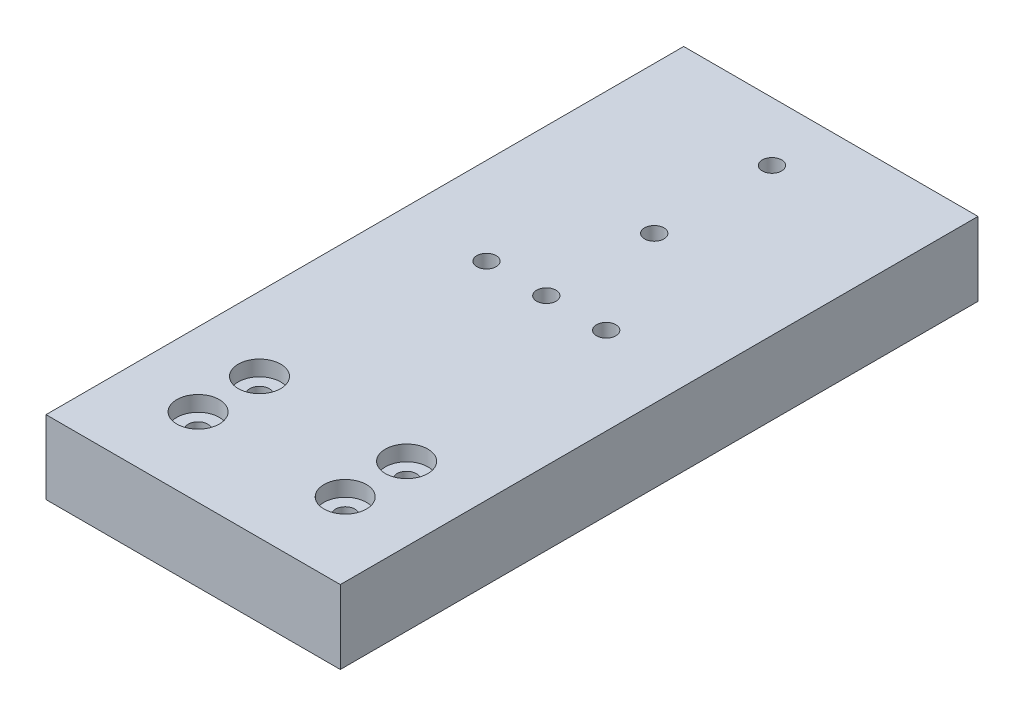
SolidWorks part; units mm, degrees
ref_plane "Front Plane" through (0, 0, 0) normal (0, 0, 1) x (1, 0, 0)
ref_plane "Top Plane" through (0, 0, 0) normal (0, 1, 0) x (1, 0, 0)
ref_plane "Right Plane" through (0, 0, 0) normal (1, 0, 0) x (0, 0, -1)
sketch "Sketch1" plane through (0, 0, 0) normal (0, 1, 0) x (1, 0, 0)
  line L1 (0, 0) -> (38.1, 0)
  line L2 (0, 0) -> (0, 82.55)
  line L3 (0, 82.55) -> (38.1, 82.55)
  line L4 (38.1, 0) -> (38.1, 82.55)
  line L5 (0, 0) -> (38.1, 82.55) construction
  line L6 (0, 82.55) -> (38.1, 0) construction
  point P4 (19.05, 41.275)
  dimension "D1" = 82.55
  dimension "D2" = 38.1
extrude "Boss-Extrude1" add sketch "Sketch1" along normal blind 9.525
sketch "Sketch2" plane through (0, 0, 0) normal (0, -1, 0) x (1, 0, 0)
  line L0 (0, -82.55) -> (0, 0) construction
  line L1 (38.1, -82.55) -> (0, -82.55) construction
  line L2 (38.1, -82.55) -> (38.1, -52.07) construction
  line L3 (38.1, -52.07) -> (0, -52.07) construction
  line L4 (0, -82.55) -> (0, -52.07) construction
  line L5 (38.1, -82.55) -> (0, -52.07) construction
  line L6 (38.1, -52.07) -> (0, -82.55) construction
  line L7 (19.05, -82.55) -> (19.05, -67.31) construction
  line L8 (19.05, -67.31) -> (19.05, -52.07) construction
  circle A0 centre (19.05, -74.93) radius 2.7749
  circle A1 centre (19.05, -59.69) radius 2.7749
  point P4 (19.05, -67.31)
  dimension "D1" = 30.48
extrude "Cut-Extrude1" cut sketch "Sketch2" against normal blind 1.999
sketch "Sketch3" plane through (0, 0, 0) normal (0, -1, 0) x (1, 0, 0)
  circle A0 centre (19.05, -74.93) radius 1.25
  circle A1 centre (19.05, -59.69) radius 1.25
  dimension "D1" = 2.5
  dimension "D2" = 2.5
extrude "Cut-Extrude2" cut sketch "Sketch3" against normal through all
sketch "Sketch4" plane through (0, 0, 0) normal (0, -1, 0) x (1, 0, 0)
  line L0 (19.05, -82.55) -> (19.05, -52.07) construction
  line L1 (38.1, -82.55) -> (0, -82.55) construction
  line L2 (19.05, -52.07) -> (3.5581, -52.07) construction
  line L3 (3.5581, -52.07) -> (3.5581, -39.37) construction
  line L4 (3.5581, -45.72) -> (19.05, -45.72) construction
  line L5 (19.05, -45.72) -> (34.5419, -45.72) construction
  circle A1 centre (19.05, -45.72) radius 2.7496
  circle A3 centre (11.304, -45.72) radius 2.7749
  circle A4 centre (26.796, -45.72) radius 2.775
  dimension "D2" = 5.5499
  dimension "D3" = 5.4991
  dimension "D4" = 5.5499
  dimension "D1" = 12.7
  dimension "D5" = 15.4919
  dimension "D6" = 30.48
extrude "Cut-Extrude3" cut sketch "Sketch4" against normal blind 1.999
sketch "Sketch5" plane through (0, 0, 0) normal (0, -1, 0) x (1, 0, 0)
  circle A1 centre (19.05, -45.72) radius 1.25
  circle A3 centre (26.796, -45.72) radius 1.25
  circle A4 centre (11.304, -45.72) radius 1.25
  dimension "D1" = 2.5
  dimension "D2" = 2.5
  dimension "D3" = 2.5
extrude "Cut-Extrude4" cut sketch "Sketch5" against normal through all
sketch "Sketch6" plane through (0, 9.525, 0) normal (0, 1, 0) x (1, 0, 0)
  line L0 (19.05, 0) -> (19.05, 10.16) construction
  line L1 (19.05, 18.1102) -> (0, 18.1102) construction
  line L2 (0, 0) -> (38.1, 0) construction
  line L3 (19.05, 10.16) -> (19.05, 18.1102) construction
  line L4 (0, 82.55) -> (0, 0) construction
  line L5 (19.05, 18.1102) -> (38.1, 18.1102) construction
  line L6 (38.1, 0) -> (38.1, 82.55) construction
  line L7 (19.05, 10.16) -> (0, 10.16) construction
  line L8 (19.05, 10.16) -> (38.1, 10.16) construction
  circle A2 centre (9.525, 18.1102) radius 2.75
  circle A3 centre (9.525, 10.16) radius 2.75
  circle A4 centre (28.575, 18.1102) radius 2.75
  circle A5 centre (28.575, 10.16) radius 2.75
  dimension "D3" = 5.5
  dimension "D4" = 5.5
  dimension "D5" = 5.5
  dimension "D6" = 5.5
  dimension "D1" = 10.16
  dimension "D2" = 7.9502
  dimension "D7" = 19.05
extrude "Cut-Extrude5" cut sketch "Sketch6" against normal blind 1.999
sketch "Sketch7" plane through (0, 9.525, 0) normal (0, 1, 0) x (1, 0, 0)
  circle A2 centre (9.525, 18.1102) radius 1.25
  circle A3 centre (9.525, 10.16) radius 1.25
  circle A4 centre (28.575, 10.16) radius 1.25
  circle A5 centre (28.575, 18.1102) radius 1.25
extrude "Cut-Extrude6" cut sketch "Sketch7" against normal blind 10
